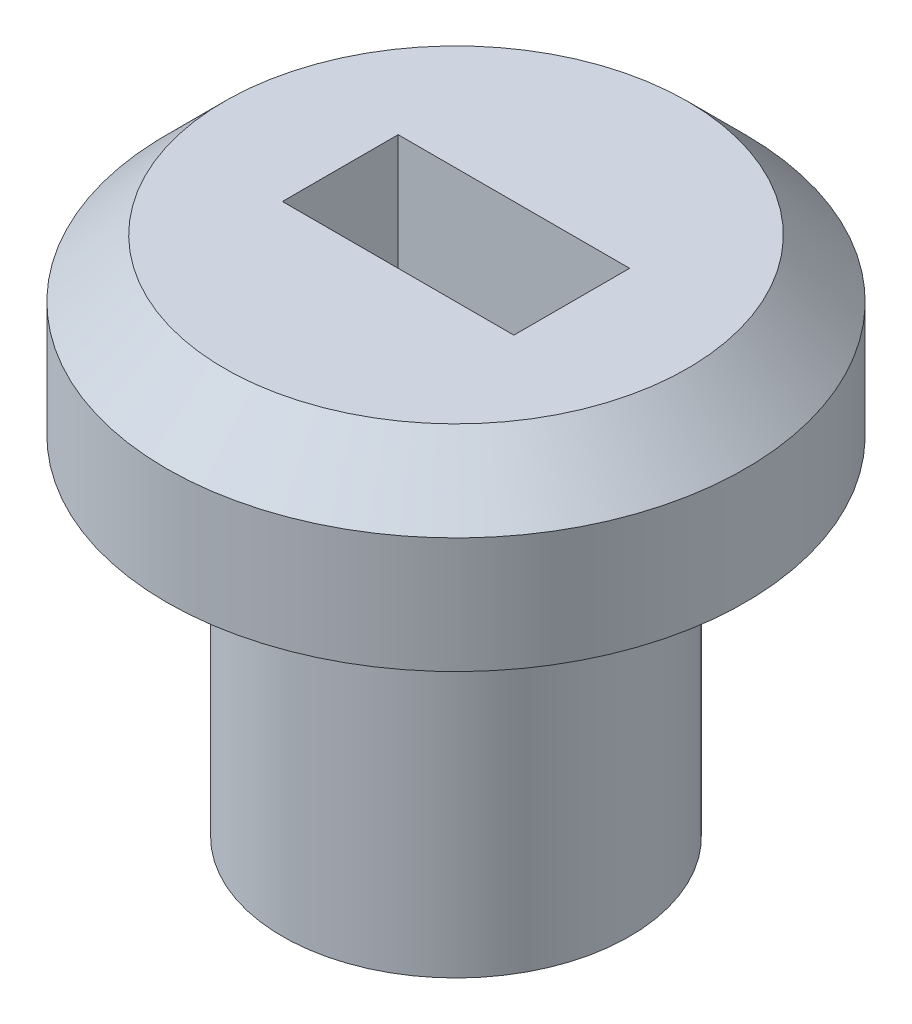
SolidWorks part; units mm, degrees
ref_plane "Front Plane" through (0, 0, 0) normal (0, 0, 1) x (1, 0, 0)
ref_plane "Top Plane" through (0, 0, 0) normal (0, 1, 0) x (1, 0, 0)
ref_plane "Right Plane" through (0, 0, 0) normal (1, 0, 0) x (0, 0, -1)
sketch "Sketch1" plane through (0, 0, 0) normal (0, 0, 1) x (1, 0, 0)
  line L0 (0, 0) -> (0, 8412.1649) construction
  line L1 (0, 3.5) -> (-0.5, 3.5)
  line L2 (-0.5, 3.5) -> (-0.5, 4.5)
  line L3 (-0.5, 4.5) -> (-2.5, 4.5)
  line L4 (-2.5, 4.5) -> (-2.5, 3)
  line L5 (-2.5, 3) -> (-1.5, 3)
  line L6 (-1.5, 3) -> (-1.5, 0)
  line L7 (-1.5, 0) -> (0, 0)
  line L8 (0, 0) -> (0, 3.5)
  point P5 (0, 0)
  point P12 (0, 0)
  point P13 (-1.5, 3.6679)
  point P14 (0, 0)
  dimension "D1" = 3
  dimension "D2" = 3
  dimension "D3" = 1
  dimension "D4" = 1.5
  dimension "D5" = 5
  dimension "D6" = 2
revolve "Revolve1" add sketch "Sketch1" angle 360 about L0
chamfer "Chamfer1" distance 0.5 angle 45 1 edges at (0, 4.5, -2.5)
sketch "Sketch2" plane through (0, 4.5, 0) normal (0, 1, 0) x (1, 0, 0)
  line L1 (-1, 0.5) -> (1, 0.5)
  line L2 (-1, 0.5) -> (-1, -0.5)
  line L3 (-1, -0.5) -> (1, -0.5)
  line L4 (1, 0.5) -> (1, -0.5)
  dimension "D1" = 1
  dimension "D2" = 0.5
  dimension "D3" = 1
  dimension "D4" = 2
extrude "Cut-Extrude1" cut sketch "Sketch2" against normal blind 1
